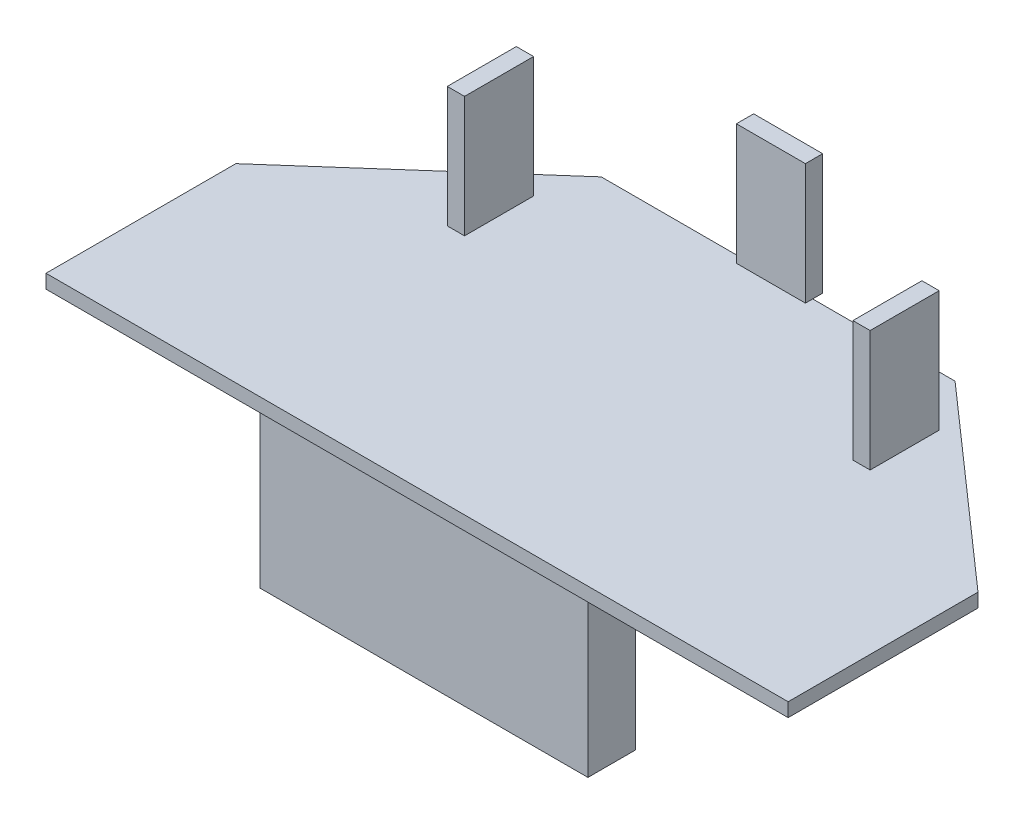
SolidWorks part; units mm, degrees
ref_plane "Front Plane" through (0, 0, 0) normal (0, 0, 1) x (1, 0, 0)
ref_plane "Top Plane" through (0, 0, 0) normal (0, 1, 0) x (1, 0, 0)
ref_plane "Right Plane" through (0, 0, 0) normal (1, 0, 0) x (0, 0, -1)
ref_plane "PZm1_6" through (0, -1.6, 0) normal (0, 1, 0) x (1, 0, 0)
sketch "Sketch1" plane through (0, -1.6, 0) normal (0, 1, 0) x (1, 0, 0)
  line L0 (-43, 0) -> (43, 0)
  line L1 (43, 0) -> (43, 22)
  line L2 (43, 22) -> (20.5, 41.8431)
  line L3 (20.5, 41.8431) -> (-20.5, 41.8431)
  line L4 (-20.5, 41.8431) -> (-43, 22)
  line L5 (-43, 22) -> (-43, 0)
extrude "PCB" add sketch "Sketch1" along normal blind 1.6
ref_plane "PZm20" through (0, -20, 0) normal (0, 1, 0) x (1, 0, 0)
sketch "Sketch2" plane through (0, -20, 0) normal (0, 1, 0) x (1, 0, 0)
  line L0 (-19, 0.8) -> (19, 0.8)
  line L1 (19, 0.8) -> (19, 6.3)
  line L2 (19, 6.3) -> (-19, 6.3)
  line L3 (-19, 6.3) -> (-19, 0.8)
extrude "J2 Header And Dupont Plugs" add sketch "Sketch2" along normal blind 20
sketch "Sketch3" plane through (0, 0, 0) normal (0, 1, 0) x (1, 0, 0)
  line L0 (-22.5, 28) -> (-22.5, 36)
  line L1 (-22.5, 36) -> (-24.5, 36)
  line L2 (-24.5, 36) -> (-24.5, 28)
  line L3 (-24.5, 28) -> (-22.5, 28)
extrude "ToF Carrier Left" add sketch "Sketch3" along normal blind 14
sketch "Sketch4" plane through (0, 0, 0) normal (0, 1, 0) x (1, 0, 0)
  line L0 (-4, 41) -> (4, 41)
  line L1 (4, 41) -> (4, 43)
  line L2 (4, 43) -> (-4, 43)
  line L3 (-4, 43) -> (-4, 41)
extrude "ToF Carrier Ahead" add sketch "Sketch4" along normal blind 14
sketch "Sketch5" plane through (0, 0, 0) normal (0, 1, 0) x (1, 0, 0)
  line L0 (22.5, 36) -> (22.5, 28)
  line L1 (22.5, 28) -> (24.5, 28)
  line L2 (24.5, 28) -> (24.5, 36)
  line L3 (24.5, 36) -> (22.5, 36)
extrude "ToF Carrier Right" add sketch "Sketch5" along normal blind 14
